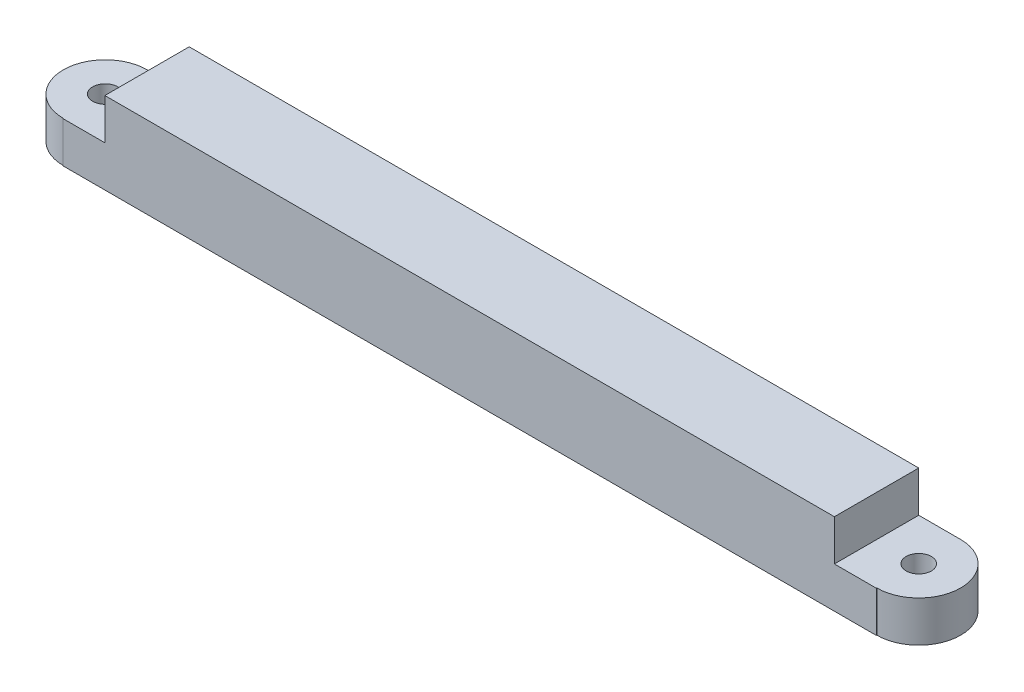
SolidWorks part; units mm, degrees
material "ABS"
ref_plane "Front Plane" through (0, 0, 0) normal (0, 0, 1) x (1, 0, 0)
ref_plane "Top Plane" through (0, 0, 0) normal (0, 1, 0) x (1, 0, 0)
ref_plane "Right Plane" through (0, 0, 0) normal (1, 0, 0) x (0, 0, -1)
sketch "Sketch1" plane through (0, 0, 0) normal (0, 1, 0) x (1, 0, 0)
  line L0 (0, 0) -> (48.45, 0)
  line L1 (0, 0) -> (0, 5)
  line L2 (48.45, -5.049) -> (0, -5.049)
  line L3 (48.45, -5.049) -> (48.45, 5)
  line L4 (0, -5.049) -> (0, 5)
  line L5 (48.45, 5) -> (0, 5)
  line L6 (48.45, -5.049) -> (0, 5) construction
  line L7 (0, -5.049) -> (48.45, 5) construction
  circle A0 centre (48.45, 0) radius 1.5
  circle A1 centre (48.45, 0) radius 5
  point P5 (24.225, -0.0245)
  dimension "D3" = 3
  dimension "D1" = 48.45
  dimension "D2" = 5
extrude "Boss-Extrude1" add sketch "Sketch1" along normal blind 9.75 contours A1 L5 L1 L0 | A1 L0 L4 L2 L3 | L3 A1 A0 | L3 A1 L0 A0 | L0 A1 L3 A0
mirror "Mirror1" about plane through (0, 0, 0) normal (1, 0, 0) of "Boss-Extrude1"
sketch "Sketch2" plane through (0, 9.75, 0) normal (0, 1, 0) x (1, 0, 0)
  line L0 (53.45, 0) -> (43.45, 0)
  line L2 (43.45, 0) -> (43.45, 5)
  line L4 (48.45, 5) -> (-48.45, 5) construction
  line L5 (43.45, 5) -> (48.45, 5)
  line L6 (43.45, 0) -> (43.45, -5.049)
  line L7 (48.45, -5.049) -> (-48.45, -5.049) construction
  line L8 (43.45, -5.049) -> (48.45, -5.049)
  arc A1 (48.45, -5) -> (48.45, 5) centre (48.45, 0) ccw construction
  arc A2 (48.45, 5) -> (53.45, 0) centre (48.45, 0) cw
  arc A3 (48.45, -5.049) -> (53.45, 0) centre (48.4007, 0) ccw
  circle M1 centre (48.45, 0) radius 1.5
  line M2 (48.45, -5.049) -> (48.45, -5)
  arc M3 (48.45, -5) -> (48.45, 5) centre (48.45, 0) ccw
  line M4 (48.45, 5) -> (-48.45, 5)
  line M7 (-48.45, -5.049) -> (48.45, -5.049)
  dimension "D1" = 10
extrude "Cut-Extrude3" cut sketch "Sketch2" against normal blind 4.875 contours L2 L0 M1 M3 M4 | L0 L6 M7 M2 M3 M1
mirror "Mirror2" about plane through (0, 0, 0) normal (1, 0, 0) of "Cut-Extrude3"
